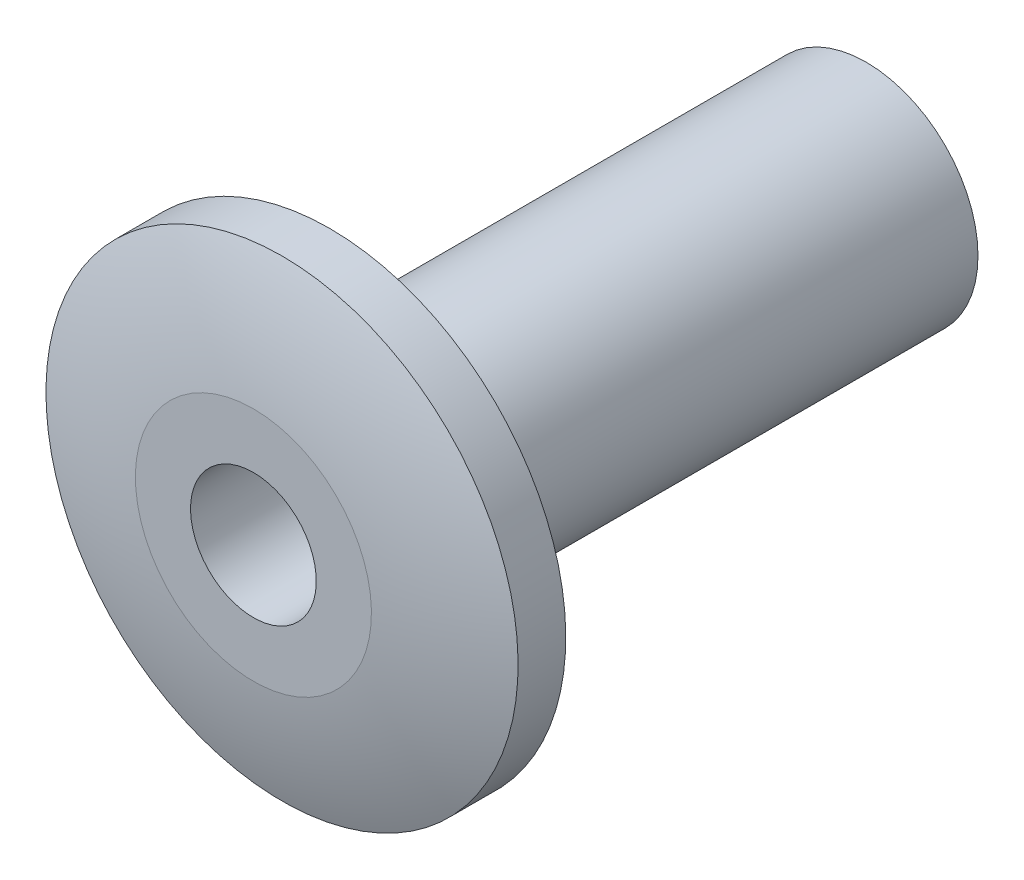
SolidWorks part; units mm, degrees
ref_plane "Front" through (0, 0, 0) normal (0, 0, 1) x (1, 0, 0)
ref_plane "Top" through (0, 0, 0) normal (0, 1, 0) x (1, 0, 0)
ref_plane "Right" through (0, 0, 0) normal (1, 0, 0) x (0, 0, -1)
sketch "Sketch1" plane through (0, 0, 0) normal (1, 0, 0) x (0, 0, -1)
  line L0 (-9.3853, 0) -> (-0.8128, 0) construction
  line L1 (-0.8128, 0) -> (0, 0) construction
  line L2 (0, 0) -> (5.715, 0) construction
  line L3 (5.715, 0) -> (6.9342, 0) construction
  line L8 (0, 2.5146) -> (0, -2.5146) construction
  line L9 (5.715, 1.1906) -> (5.715, -1.1906) construction
  dimension "Length" = 5.715
  dimension "Head Height" = 0.8128
  dimension "D5" = 1.2192
  dimension "D9" = 8.5725
  dimension "Diameter" = 2.3813
  dimension "Head Diameter" = 5.0292
sketch "Sketch2" plane through (0, 0, 0) normal (1, 0, 0) x (0, 0, -1)
  line L0 (-9.3853, 0.5953) -> (-9.3853, 0) construction
  line L1 (-9.3853, 0.5953) -> (0, 0.5953) construction
  line L2 (0, 2.5146) -> (0, -2.5146) construction
  line L3 (0, 0) -> (0, 2.5146) construction
  line L4 (-0.8128, 0) -> (-0.8128, -1.8472) construction
  line L5 (5.715, 1.1906) -> (0, 1.1906)
  line L6 (5.715, 1.1906) -> (5.715, 0) construction
  line L7 (6.9342, 0) -> (6.9342, 1.1906) construction
  line L8 (5.715, 1.1906) -> (5.715, 0)
  line L9 (6.9342, 1.1906) -> (5.715, 1.1906) construction
  line L10 (-0.8128, 0.6697) -> (-0.8128, 1.2573)
  line L11 (5.715, 0) -> (6.9342, 0) construction
  line L12 (5.715, 0) -> (0.5715, 0)
  line L13 (-0.8128, 0.5953) -> (-0.8128, 0) construction
  line L14 (5.715, 1.1906) -> (5.715, 0) construction
  line L15 (5.715, 1.1906) -> (5.715, 0) construction
  line L16 (5.715, 0) -> (5.715, 1.1906) construction
  line L17 (5.715, 1.1906) -> (5.715, 0) construction
  line L18 (5.715, 0) -> (5.715, 1.1906) construction
  line L19 (0, 1.1906) -> (0, 2.5146)
  line L20 (-0.8128, 0.6697) -> (0, 0.6697)
  line L21 (-9.3853, 0.6697) -> (0, 0.6697) construction
  line L22 (0, 2.5146) -> (-0.508, 2.5146)
  line L23 (0, 0.6697) -> (0.5715, 0.6697)
  line L24 (0.5715, 0.6697) -> (0.5715, 0)
  arc A0 (6.9342, 0) -> (5.715, 0.9525) centre (5.9525, 0) ccw construction
  arc A2 (-0.508, 2.5146) -> (-0.8128, 1.2573) centre (4.6635, 0.5953) ccw
  dimension "D3" = 0.508
  dimension "D1" = 0.5953
  dimension "D2" = 0.5715
  dimension "D5" = 0.9525
  dimension "D6" = 1.2573
  dimension "D4" = 0.0744
revolve "Revolve1" add sketch "Sketch2" angle 360 about L12
sketch "Sketch7" plane through (0, 0, 0) normal (1, 0, 0) x (0, 0, -1)
  line L0 (-8.8206, 0.5953) -> (0.5715, 0.5953)
  line L1 (0.5715, 0.6697) -> (0.5715, 0) construction
  line L2 (0.5715, 0.5953) -> (0.5715, 0)
  line L3 (0.5715, 0) -> (-9.3853, 0)
  line L5 (-9.2923, 0.1995) -> (-8.8206, 0.5953)
  arc A0 (-9.3853, 0) -> (-9.2923, 0.1995) centre (-9.1249, 0) cw
  dimension "D1" = 0.2604
  dimension "D2" = 40
revolve "Revolve2" [suppressed] add sketch "Sketch7" angle 360 about L0
sketch "Sketch8" plane through (0, 0, 0) normal (1, 0, 0) x (0, 0, -1)
  line L1 (5.715, 0.9525) -> (5.715, 0)
  line L2 (5.715, 0) -> (6.9342, 0) construction
  line L3 (6.9342, 0) -> (5.9525, 0) construction
  line L4 (6.6888, 0) -> (5.715, 0)
  line L5 (5.715, 0.9525) -> (6.0713, 0.9525) construction
  arc A0 (6.9342, 0) -> (5.715, 0.9525) centre (5.9525, 0) ccw construction
  arc A1 (6.0713, 0.9745) -> (5.715, 0.9525) centre (5.9525, 0) ccw
  arc A2 (6.0713, 0.9745) -> (6.6888, 0) centre (5.6111, 0) cw
  circle A3 centre (5.9525, 0) radius 0.9817 construction
  point P7 (6.6888, 0)
  point P8 (6.4434, 0)
  point P9 (6.1979, 0)
  point P12 (5.8338, 0.9525)
  point P13 (5.9525, 0.9525)
revolve "Revolve3" [suppressed] add sketch "Sketch8" angle 360 about L3
sketch "Sketch3" [suppressed] plane through (0, 0, 0) normal (0, 1, 0) x (1, 0, 0)
  line L0 (-0.7985, -7.6465) -> (-0.1657, -9.3853)
  line L1 (-0.1657, -9.3853) -> (0.1657, -9.3853)
  line L3 (0, -9.3853) -> (0, -9.8933) construction
  line L4 (0.1995, -9.2923) -> (-0.1995, -9.2923) construction
  line L5 (-0.7985, -7.6465) -> (-0.7985, -9.8933)
  line L6 (-0.7985, -9.8933) -> (0.7985, -9.8933)
  line L7 (0.7985, -9.8933) -> (0.7985, -7.6465)
  line L8 (-0.5953, 0.5715) -> (-0.5953, -8.8206) construction
  line L9 (0, -9.3853) -> (0, -0.8128) construction
  line L10 (0.1657, -9.3853) -> (0.7985, -7.6465)
  line L11 (-0.5953, -8.8206) -> (-0.1995, -9.2923) construction
  arc A0 (-0.1995, -9.2923) -> (0.1995, -9.2923) centre (0, -9.1249) ccw construction
  point P11 (-0.1995, -9.2923)
  point P25 (0, -9.3853)
  dimension "D1" = 40
  dimension "D2" = 0.2032
  dimension "D3" = 0.508
extrude "Cut-Extrude1" [suppressed] cut sketch "Sketch3" against normal through all both and the other way through all
pattern_circular "CirPattern1" [suppressed] count 2 every 90 about axis through (0, 0, 9.3853) along (0, 0, -1)
sketch "Sketch9" [suppressed] plane through (0, 0, 0) normal (0, 1, 0) x (1, 0, 0)
  line L0 (0, -9.3853) -> (0, 19.9517) construction
  line L1 (0, 5.715) -> (0, 6.9342) construction
  line L2 (2.5146, 0) -> (-2.5146, 0) construction
  line L3 (1.5316, 0) -> (1.6066, 0)
  line L4 (1.5316, 0) -> (1.5316, 0.0254)
  line L5 (1.5316, 0.0254) -> (1.6066, 0.0254)
  line L6 (1.6066, 0) -> (1.6066, 0.0254)
  line L8 (1.739, 0) -> (1.8139, 0)
  line L9 (1.739, 0) -> (1.739, 0.0254)
  line L10 (1.739, 0.0254) -> (1.8139, 0.0254)
  line L11 (1.8139, 0) -> (1.8139, 0.0254)
  line L12 (1.9238, 0) -> (1.9987, 0)
  line L13 (1.9238, 0) -> (1.9238, 0.0254)
  line L14 (1.9238, 0.0254) -> (1.9987, 0.0254)
  line L15 (1.9987, 0) -> (1.9987, 0.0254)
  line L16 (2.1911, 0) -> (2.266, 0)
  line L17 (2.1911, 0) -> (2.1911, 0.0254)
  line L18 (2.1911, 0.0254) -> (2.266, 0.0254)
  line L19 (2.266, 0) -> (2.266, 0.0254)
  line L20 (1.4342, 0) -> (1.3592, 0)
  line L21 (1.4342, 0) -> (1.4342, 0.0254)
  line L22 (1.4342, 0.0254) -> (1.3592, 0.0254)
  line L23 (1.3592, 0) -> (1.3592, 0.0254)
  point P24 (2.2286, 0.0254)
  point P25 (1.9613, 0.0254)
  point P26 (1.7764, 0.0254)
  point P27 (1.5691, 0.0254)
  point P32 (1.3967, 0.0254)
  dimension "D1" = 0.0749
  dimension "D2" = 0.0254
  dimension "D3" = 4.4571
  dimension "D4" = 3.9226
  dimension "D5" = 3.5528
  dimension "D6" = 3.1382
  dimension "D7" = 2.7934
revolve "Revolve4" [suppressed] add sketch "Sketch9" angle 360 about L0
equation "\"D5@Sketch1\" = \"Head Height@Sketch1\" * 1.5"
equation "\"D9@Sketch1\" = \"Length@Sketch1\" * 1.5"
equation "\"D1@Sketch2\"=\"Diameter@Sketch1\"/4"
equation "\"D4@Sketch2\"=\"D1@Sketch2\"/8"
equation "\"D2@Sketch2\"=\"Length@Sketch1\"/10"
equation "\"D5@Sketch2\"=\"Diameter@Sketch1\"*.8/2"
equation "\"D1@Sketch7\"=(\"D1@Sketch2\"-\"D4@Sketch2\")*2*.25"
equation "\"D6@Sketch2\"=\"Head Diameter@Sketch1\"/2*.5"
equation "\"D7@Sketch9\"=.15566*(\"Head Diameter@Sketch1\"-\"Diameter@Sketch1\")+\"Diameter@Sketch1\""
equation "\"D3@Sketch9\"=.7839623*(\"Head Diameter@Sketch1\"-\"Diameter@Sketch1\")+\"Diameter@Sketch1\""
equation "\"D1@Sketch9\"=.028302*(\"Head Diameter@Sketch1\"-\"Diameter@Sketch1\")"
equation "\"D6@Sketch9\"=.285849*(\"Head Diameter@Sketch1\"-\"Diameter@Sketch1\")+\"Diameter@Sketch1\""
equation "\"D5@Sketch9\"=.4424528*(\"Head Diameter@Sketch1\"-\"Diameter@Sketch1\")+\"Diameter@Sketch1\""
equation "\"D4@Sketch9\"=.582075*(\"Head Diameter@Sketch1\"-\"Diameter@Sketch1\")+\"Diameter@Sketch1\""
